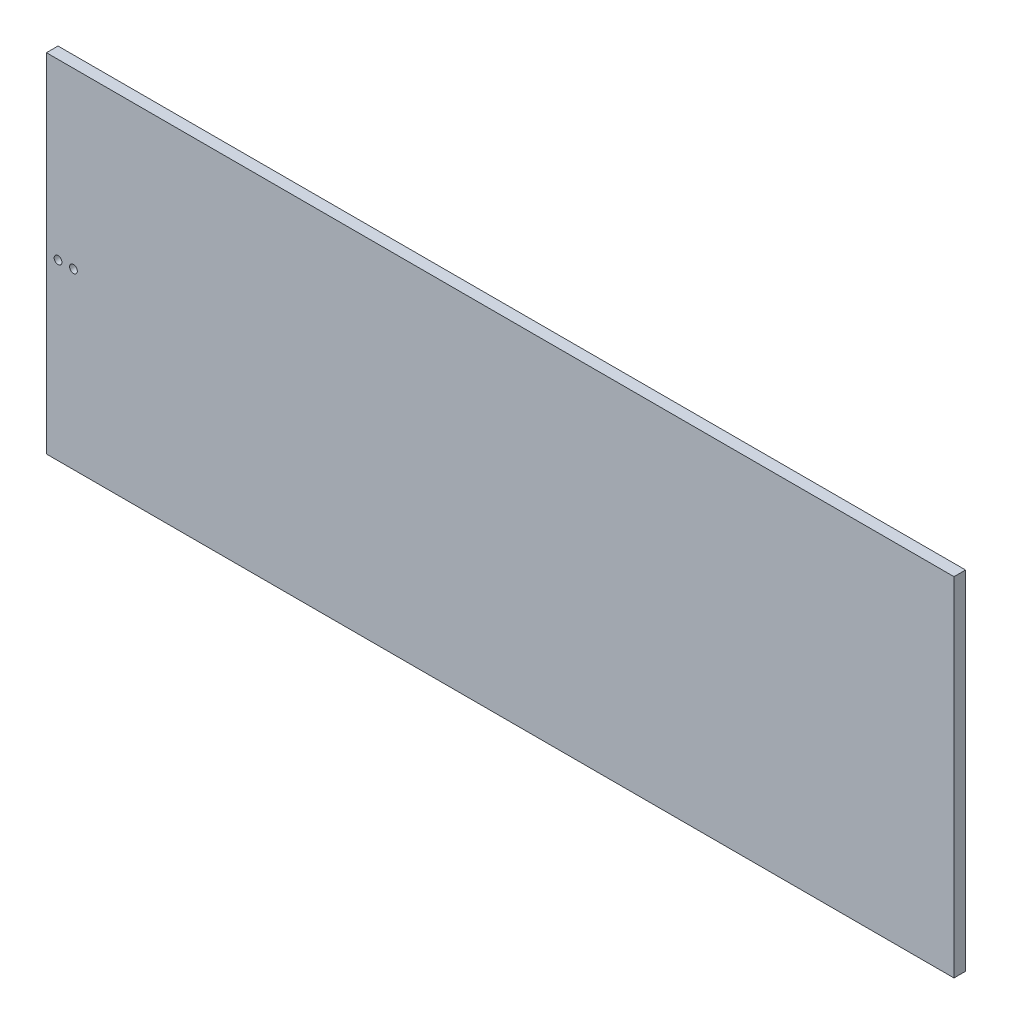
SolidWorks part; units mm, degrees
ref_plane "前视基准面" through (0, 0, 0) normal (0, 0, 1) x (1, 0, 0)
ref_plane "上视基准面" through (0, 0, 0) normal (0, 1, 0) x (1, 0, 0)
ref_plane "右视基准面" through (0, 0, 0) normal (1, 0, 0) x (0, 0, -1)
sketch "草图1" plane through (0, 0, 0) normal (0, 0, 1) x (1, 0, 0)
  line L1 (-117.5, -45) -> (117.5, -45)
  line L2 (-117.5, -45) -> (-117.5, 45)
  line L3 (-117.5, 45) -> (117.5, 45)
  line L4 (117.5, -45) -> (117.5, 45)
  line L5 (-117.5, -45) -> (117.5, 45) construction
  line L6 (-117.5, 45) -> (117.5, -45) construction
  point P0 (0, 0)
  dimension "D1" = 235
  dimension "D2" = 90
extrude "凸台-拉伸1" add sketch "草图1" along normal blind 3
sketch "草图2" plane through (-117.5, 0, 0) normal (-1, 0, 0) x (0, 0, 1)
  line L0 (0, 0) -> (3, 0) construction
  line L1 (0, 45) -> (0, -45) construction
  line L2 (3, 45) -> (3, -45) construction
  line L4 (0, 4) -> (1, 4)
  line L5 (0, 4) -> (0, -4)
  line L6 (0, -4) -> (1, -4)
  line L7 (1, 4) -> (1, -4)
  dimension "D1" = 1
  dimension "D2" = 8
extrude "切除-拉伸1" cut sketch "草图2" against normal blind 10
sketch "草图3" plane through (0, 0, 1) normal (0, 0, -1) x (-1, 0, 0)
  line L0 (117.5, 0) -> (107.5, 0) construction
  line L1 (117.5, -4) -> (117.5, 4) construction
  line L2 (107.5, -4) -> (107.5, 4) construction
  circle A0 centre (110.5, 0) radius 1
  circle A1 centre (114.5, 0) radius 1
  dimension "D1" = 2
  dimension "D2" = 2
  dimension "D3" = 3
  dimension "D4" = 4
extrude "切除-拉伸2" cut sketch "草图3" against normal blind 10
